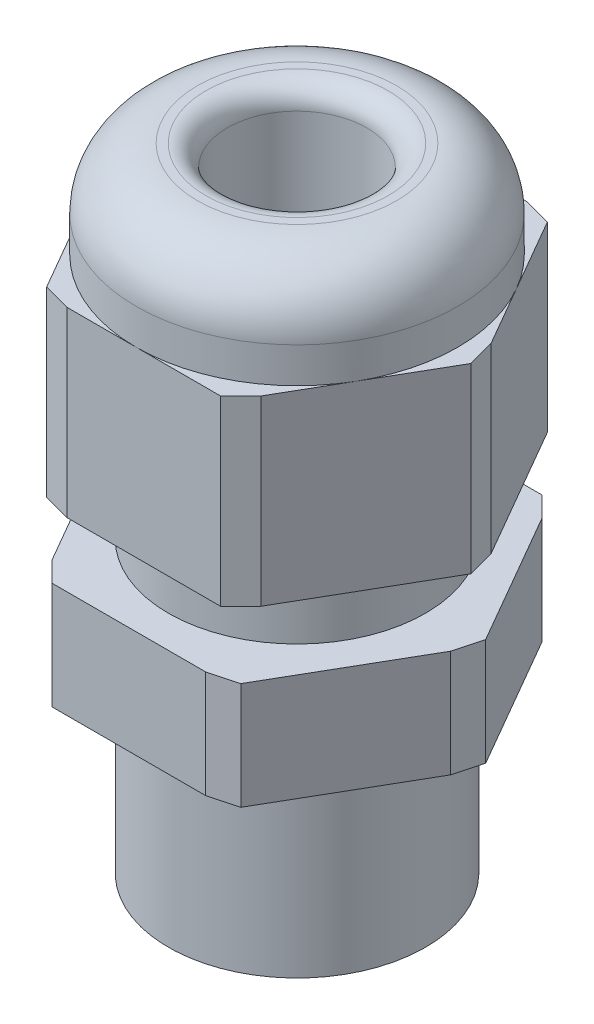
SolidWorks part; units mm, degrees
ref_plane "Front Plane" through (0, 0, 0) normal (0, 0, 1) x (1, 0, 0)
ref_plane "Top Plane" through (0, 0, 0) normal (0, 1, 0) x (1, 0, 0)
ref_plane "Right Plane" through (0, 0, 0) normal (1, 0, 0) x (0, 0, -1)
sketch "Sketch1" plane through (0, 0, 0) normal (0, 1, 0) x (1, 0, 0)
  line L1 (8.6603, 0) -> (4.3301, 7.5)
  line L2 (4.3301, 7.5) -> (-4.3301, 7.5)
  line L3 (-4.3301, 7.5) -> (-8.6603, 0)
  line L4 (-8.6603, 0) -> (-4.3301, -7.5)
  line L5 (-4.3301, -7.5) -> (4.3301, -7.5)
  line L6 (4.3301, -7.5) -> (8.6603, 0)
  circle A0 centre (0, 0) radius 7.5 construction
  dimension "D1" = 15
extrude "Boss-Extrude1" add sketch "Sketch1" along normal blind 8.5
sketch "Sketch2" plane through (0, 0, 0) normal (1, 0, 0) x (0, 0, -1)
  line L0 (-7.5, 8.5) -> (-7.5, 10.15)
  line L1 (-4.65, 13) -> (0, 13)
  line L2 (0, 13) -> (0, 8.5)
  line L3 (0, 8.5) -> (-7.5, 8.5)
  arc A0 (-7.5, 10.15) -> (-4.65, 13) centre (-4.65, 10.15) cw
  dimension "D1" = 4.5
  dimension "D2" = 2.85
  dimension "D3" = 4.65
revolve "Revolve1" add sketch "Sketch2" angle 360 about L2
sketch "Sketch4" plane through (0, 0, 0) normal (0, 1, 0) x (1, 0, 0)
  circle A0 centre (0, 0) radius 6
  dimension "D1" = 12
extrude "Boss-Extrude2" add sketch "Sketch4" against normal blind 3
sketch "Sketch5" plane through (0, -3, 0) normal (0, -1, 0) x (1, 0, 0)
  line L6 (8.6603, 0) -> (4.3301, 7.5)
  line L7 (4.3301, 7.5) -> (-4.3301, 7.5)
  line L8 (-4.3301, 7.5) -> (-8.6603, 0)
  line L9 (-8.6603, 0) -> (-4.3301, -7.5)
  line L10 (-4.3301, -7.5) -> (4.3301, -7.5)
  line L11 (4.3301, -7.5) -> (8.6603, 0)
  line L12 (8.6603, 0) -> (4.3301, 7.5)
  line L13 (4.3301, 7.5) -> (-4.3301, 7.5)
  line L14 (-4.3301, 7.5) -> (-8.6603, 0)
  line L15 (-8.6603, 0) -> (-4.3301, -7.5)
  line L16 (-4.3301, -7.5) -> (4.3301, -7.5)
  line L17 (4.3301, -7.5) -> (8.6603, 0)
  dimension "D1" = 0
extrude "Boss-Extrude3" add sketch "Sketch5" along normal blind 5
sketch "Sketch6" plane through (0, -8, 0) normal (0, -1, 0) x (1, 0, 0)
  circle A0 centre (0, 0) radius 6
  dimension "D1" = 12
extrude "Boss-Extrude4" add sketch "Sketch6" along normal blind 8.5
sketch "Sketch3" plane through (0, 13, 0) normal (0, 1, 0) x (1, 0, 0)
  circle A0 centre (0, 0) radius 3.25
  dimension "D1" = 6.5
extrude "Cut-Extrude1" cut sketch "Sketch3" against normal through all
fillet "Fillet1" radius 1 1 edges at (0, 13, 3.25)
chamfer "Chamfer1" distance 0.4 angle 45 12 edges at (-4.3301, -5.5, 7.5) (-8.6603, -5.5, 0) (-4.3301, -5.5, -7.5) (4.3301, -5.5, -7.5) (4.3301, -5.5, 7.5) (8.6603, -5.5, 0) (4.3301, 4.25, 7.5) (-4.3301, 4.25, 7.5) (-8.6603, 4.25, 0) (-4.3301, 4.25, -7.5) (4.3301, 4.25, -7.5) (8.6603, 4.25, 0)
